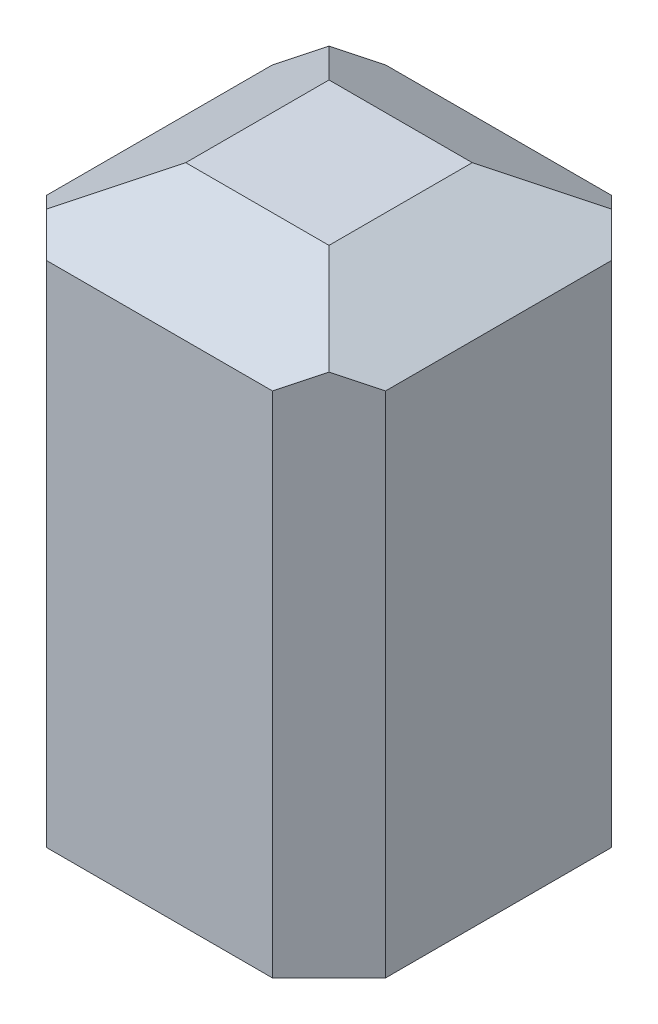
SolidWorks part; units mm, degrees
material "PE Low/Medium Density"
ref_plane "Front" through (0, 0, 0) normal (0, 0, 1) x (1, 0, 0)
ref_plane "Top" through (0, 0, 0) normal (0, 1, 0) x (1, 0, 0)
ref_plane "Right" through (0, 0, 0) normal (1, 0, 0) x (0, 0, -1)
sketch "Sketch11" plane through (0, 0, 0) normal (0, 1, 0) x (1, 0, 0)
  line L0 (-3, -3) -> (3, 3) construction
  line L1 (-3, 3) -> (3, 3)
  line L2 (-3, 3) -> (-3, -3)
  line L3 (-3, -3) -> (3, -3)
  line L4 (3, 3) -> (3, -3)
  dimension "D1" = 6
  dimension "D2" = 6
extrude "Extrude8" add sketch "Sketch11" along normal blind 10
chamfer "Chamfer1" distance 1 2 edges at (3, 5, -3) (-3, 5, 3)
chamfer "Chamfer2" distance 1 2 edges at (-3, 5, -3) (3, 5, 3)
chamfer "Chamfer3" distance 1 angle 60 2 edges at (0, 10, 3) (0, 10, -3)
chamfer "Chamfer4" distance 1 angle 60 2 edges at (3, 10, 0) (-3, 10, 0)
